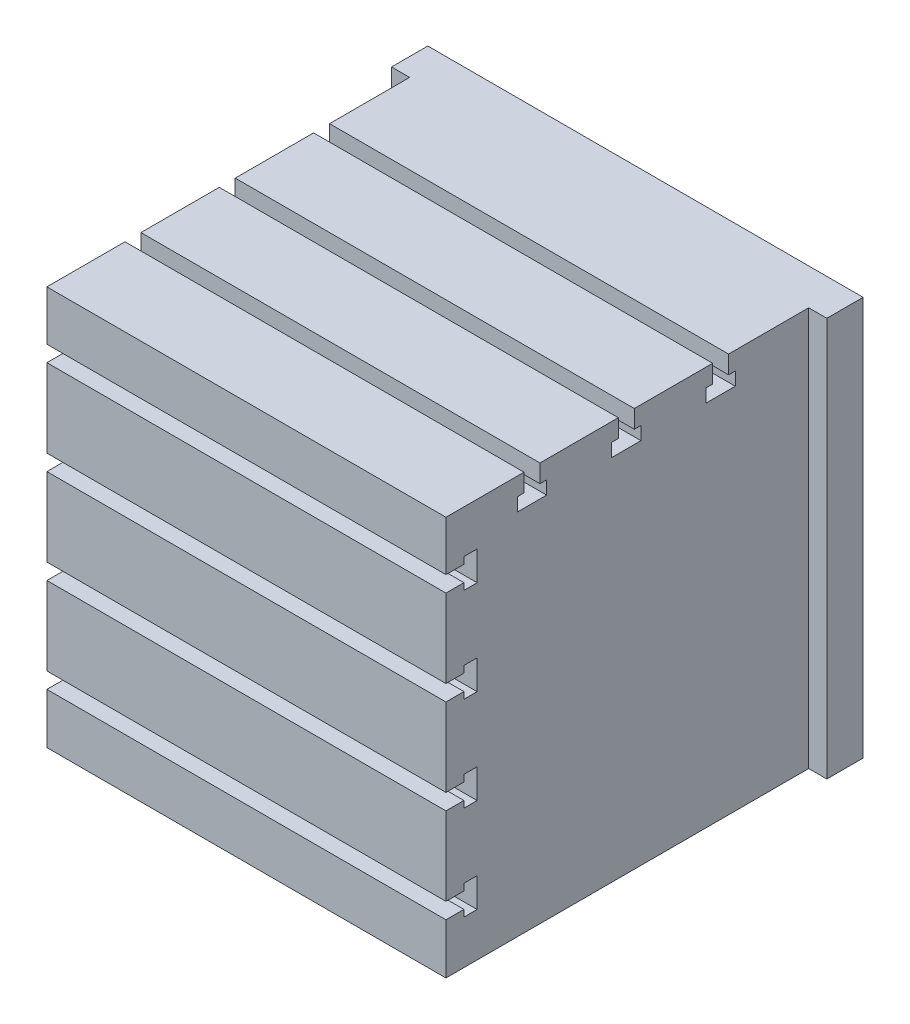
SolidWorks part; units mm, degrees
ref_plane "Front Plane" through (0, 0, 0) normal (0, 0, 1) x (1, 0, 0)
ref_plane "Top Plane" through (0, 0, 0) normal (0, 1, 0) x (1, 0, 0)
ref_plane "Right Plane" through (0, 0, 0) normal (1, 0, 0) x (0, 0, -1)
sketch "Sketch1" plane through (0, 0, 0) normal (0, 1, 0) x (1, 0, 0)
  line L0 (300, 0) -> (-300, 0)
  line L1 (-300, 0) -> (-300, -50)
  line L2 (-300, -50) -> (-275, -50)
  line L3 (-275, -50) -> (-275, -550)
  line L4 (-275, -550) -> (275, -550)
  line L5 (275, -550) -> (275, -50)
  line L6 (275, -50) -> (300, -50)
  line L7 (300, -50) -> (300, 0)
  line L8 (0, 261.9612) -> (0, -838.0388) construction
  dimension "D1" = 550
  dimension "D2" = 50
  dimension "D3" = 550
  dimension "D4" = 600
extrude "Boss-Extrude1" add sketch "Sketch1" against normal blind 550
sketch "Sketch2" plane through (-275, 0, 0) normal (-1, 0, 0) x (0, 0, 1)
  line L0 (442.4, 0) -> (442.4, -24.8)
  line L1 (50, 0) -> (550, 0) construction
  line L2 (442.4, -24.8) -> (451.6, -24.8)
  line L3 (451.6, -24.8) -> (451.6, -43)
  line L4 (451.6, -43) -> (411.2, -43)
  line L5 (411.2, -43) -> (411.2, -24.8)
  line L6 (411.2, -24.8) -> (420.4, -24.8)
  line L7 (420.4, -24.8) -> (420.4, 0)
  line L8 (420.4, 0) -> (442.4, 0)
  line L9 (431.4, 11.4794) -> (431.4, -81.5523) construction
  line L11 (550, -550) -> (550, 0) construction
  dimension "D1" = 22
  dimension "D2" = 40.4
  dimension "D3" = 43
  dimension "D4" = 24.8
  dimension "D5" = 118.6
  dimension "D6" = 107.6
extrude "Cut-Extrude1" cut sketch "Sketch2" against normal up to next
sketch "Sketch3" plane through (-275, 0, 0) normal (-1, 0, 0) x (0, 0, 1)
  line L0 (441.0726, -79.5) -> (637.4708, -79.5) construction
  line L1 (550, -550) -> (550, 0) construction
  line L2 (550, -90.5) -> (550, -68.5)
  line L3 (550, -68.5) -> (525.2, -68.5)
  line L4 (525.2, -68.5) -> (525.2, -59.3)
  line L5 (525.2, -59.3) -> (507, -59.3)
  line L6 (507, -59.3) -> (507, -99.7)
  line L7 (507, -99.7) -> (525.2, -99.7)
  line L8 (525.2, -99.7) -> (525.2, -90.5)
  line L9 (525.2, -90.5) -> (550, -90.5)
  line L11 (442.4, 0) -> (550, 0) construction
  dimension "D1" = 22
  dimension "D2" = 40.4
  dimension "D3" = 43
  dimension "D4" = 24.8
  dimension "D5" = 79.5
  dimension "D6" = 68.5
extrude "Cut-Extrude2" cut sketch "Sketch3" against normal up to next
pattern_linear "LPattern1" count 3 spacing 130 along (0, 0, -1) of "Cut-Extrude1"
pattern_linear "LPattern2" count 4 spacing 130 along (0, -1, 0) of "Cut-Extrude2"
